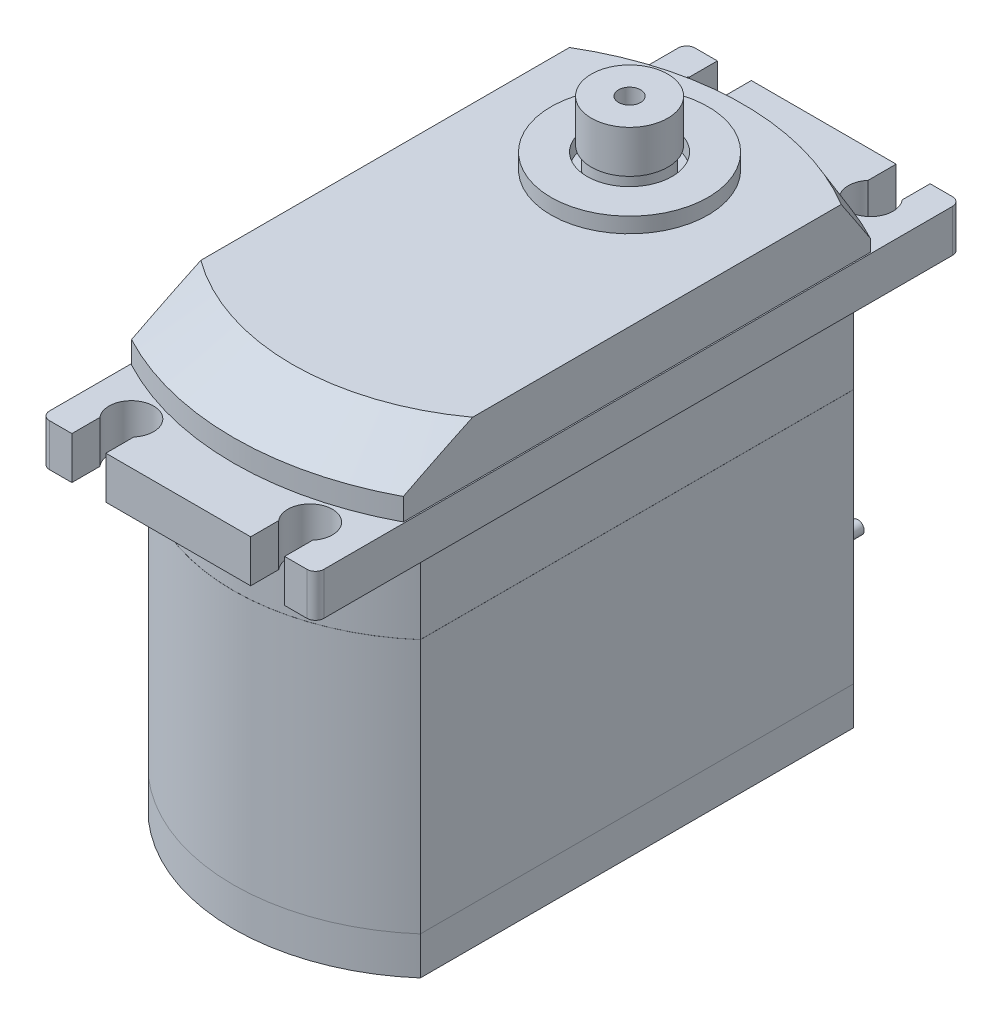
SolidWorks part; units mm, degrees
ref_plane "Front Plane" through (0, 0, 0) normal (0, 0, 1) x (1, 0, 0)
ref_plane "Top Plane" through (0, 0, 0) normal (0, 1, 0) x (1, 0, 0)
ref_plane "Right Plane" through (0, 0, 0) normal (1, 0, 0) x (0, 0, -1)
sketch "Sketch1" plane through (0, 0, 0) normal (0, 1, 0) x (1, 0, 0)
  line L1 (-16, 31.5) -> (16, 31.5)
  line L2 (-16, 31.5) -> (-16, -31.5)
  line L3 (-16, -31.5) -> (16, -31.5)
  line L4 (16, 31.5) -> (16, -31.5)
  line L5 (-16, 31.5) -> (16, -31.5) construction
  line L6 (-16, -31.5) -> (16, 31.5) construction
  point P0 (0, 0)
  dimension "D1" = 63
  dimension "32" = 32
extrude "Boss-Extrude1" add sketch "Sketch1" along normal blind 35
sketch "Sketch2" plane through (0, 35, 0) normal (0, 1, 0) x (1, 0, 0)
  line L1 (-16.5, 31.5) -> (16.5, 31.5)
  line L2 (-16.5, 31.5) -> (-16.5, -31.5)
  line L3 (-16.5, -31.5) -> (16.5, -31.5)
  line L4 (16.5, 31.5) -> (16.5, -31.5)
  line L5 (-16.5, 31.5) -> (16.5, -31.5) construction
  line L6 (-16.5, -31.5) -> (16.5, 31.5) construction
  point P0 (0, 0)
  dimension "D1" = 63
  dimension "sfds" = 33
extrude "Boss-Extrude2" add sketch "Sketch2" along normal blind 7.5
sketch "Sketch4" plane through (0, 42.5, 0) normal (0, 1, 0) x (1, 0, 0)
  line L0 (10.525, -33) -> (16.15, -33)
  line L1 (-16.15, -38) -> (16.15, -38)
  line L2 (-16.15, -38) -> (-16.15, 38)
  line L3 (-16.15, 38) -> (16.15, 38)
  line L4 (16.15, -38) -> (16.15, 38)
  line L5 (-16.15, -38) -> (16.15, 38) construction
  line L6 (-16.15, 38) -> (16.15, -38) construction
  line L7 (-10.525, -33) -> (-16.15, -33)
  line L8 (-10.525, 33) -> (-16.15, 33)
  line L9 (10.525, 33) -> (16.15, 33)
  line L10 (-10.525, -33) -> (-10.525, -38)
  line L11 (10.525, -33) -> (10.525, -38)
  line L12 (-10.525, 33) -> (-10.525, 38)
  line L13 (10.525, 33) -> (10.525, 38)
  line L14 (-12.525, -33) -> (-8.525, -33)
  line L15 (-8.525, -33) -> (-8.525, -38)
  line L16 (-12.525, -33) -> (-12.525, -38)
  line L17 (8.525, -33) -> (12.525, -33)
  line L18 (8.525, -33) -> (8.525, -38)
  line L19 (12.525, -33) -> (12.525, -38)
  line L20 (8.525, 33) -> (12.525, 33)
  line L21 (8.525, 33) -> (8.525, 38)
  line L22 (12.525, 33) -> (12.525, 38)
  line L23 (-12.525, 33) -> (-8.525, 33)
  line L24 (-8.525, 33) -> (-8.525, 38)
  line L25 (-12.525, 33) -> (-12.525, 38)
  circle A0 centre (-10.525, -33) radius 2.625
  circle A1 centre (10.525, -33) radius 2.625
  circle A2 centre (-10.525, 33) radius 2.625
  circle A3 centre (10.525, 33) radius 2.625
  point P0 (0, 0)
  point P26 (-10.525, -33)
  point P31 (10.525, -33)
  point P36 (10.525, 33)
  point P41 (-10.525, 33)
  line M18 (16.5, 31.5) -> (-16.5, 31.5)
  line M20 (-16.5, -31.5) -> (16.5, -31.5)
  dimension "D3" = 5.25
  dimension "D1" = 32.3
  dimension "D2" = 76
  dimension "D4" = 5.625
  dimension "D5" = 5
  dimension "D6" = 4
extrude "Boss-Extrude3" add sketch "Sketch4" along normal blind 5 contours A3 A2 L2 A0 A1 L4 M18 M20 | A1 A0 L15 L1 L18 M20 | A1 L0 L4 M20 | A1 L19 L1 L4 L0 | A0 L7 L2 L1 L16 | A0 L2 L7 M20 | A3 L9 L4 L3 L22 | A3 L4 L9 M18 | A3 L21 L3 L24 A2 M18 | A2 L8 L2 M18 | A2 L25 L3 L2 L8
sketch "Sketch5" plane through (0, 0, 0) normal (0, -1, 0) x (1, 0, 0)
  line L0 (-16, 31.5) -> (-16, 25.5) construction
  line L1 (-16, -31.5) -> (-16, 31.5) construction
  line L2 (-16, 25.5) -> (16, 25.5) construction
  line L3 (16, 31.5) -> (16, -31.5) construction
  line L4 (-16, 25.5) -> (16, 25.5)
  line L5 (0, 0) -> (26.1887, 0) construction
  line L6 (-16, -25.5) -> (16, -25.5)
  arc A0 (-16, 25.5) -> (16, 25.5) centre (0, 7.1667) cw
  arc A1 (-16, -25.5) -> (16, -25.5) centre (0, -7.1667) ccw
  line M3 (16, -31.5) -> (16, 31.5)
  line M4 (16, 31.5) -> (-16, 31.5)
  line M5 (-16, 31.5) -> (-16, -31.5)
  line M6 (-16, -31.5) -> (16, -31.5)
  dimension "D1" = 6
extrude "Cut-Extrude2" cut sketch "Sketch5" against normal up to surface (42.5 mm away) contours A0 M4 M3 | A0 M5 M4 | A1 M5 M6 | A1 M6 M3 up to face at (14.1148, 42.5, -34.7453)
sketch "Sketch6" plane through (-16.5, 0, 0) normal (-1, 0, 0) x (0, 0, 1)
  line L1 (-31.5, 42.5) -> (31.5, 42.5)
  line L2 (-31.5, 42.5) -> (-31.5, 35)
  line L3 (-31.5, 35) -> (31.5, 35)
  line L4 (31.5, 42.5) -> (31.5, 35)
extrude "Cut-Extrude3" cut sketch "Sketch6" against normal blind 0.5
sketch "Sketch7" plane through (16.5, 0, 0) normal (1, 0, 0) x (0, 0, -1)
  line L1 (-31.5, 42.5) -> (31.5, 42.5)
  line L2 (-31.5, 42.5) -> (-31.5, 35)
  line L3 (-31.5, 35) -> (31.5, 35)
  line L4 (31.5, 42.5) -> (31.5, 35)
extrude "Cut-Extrude4" cut sketch "Sketch7" against normal blind 0.5
sketch "Sketch8" plane through (0, 47.5, 0) normal (0, 1, 0) x (1, 0, 0)
  line L0 (-16, -31.5) -> (-16, -27.5) construction
  line L1 (-16, -31.5) -> (16, -31.5)
  line L2 (-16, -31.5) -> (-16, 31.5)
  line L3 (-16, 31.5) -> (16, 31.5)
  line L4 (16, -31.5) -> (16, 31.5)
  line L5 (-16, -31.5) -> (16, 31.5) construction
  line L6 (-16, 31.5) -> (16, -31.5) construction
  line L7 (-16, -27.5) -> (16, -27.5) construction
  line L8 (0, 0) -> (-24.3268, 0) construction
  line L9 (-16, -27.5) -> (16, -27.5)
  line L10 (-16, 27.5) -> (16, 27.5)
  arc A0 (-16, -27.5) -> (16, -27.5) centre (0, 2.5) ccw
  arc A1 (-16, 27.5) -> (16, 27.5) centre (0, -2.5) cw
  point P0 (0, 0)
  dimension "D1" = 32
  dimension "D2" = 63
  dimension "4" = 4
extrude "Boss-Extrude4" add sketch "Sketch8" along normal blind 6.6 contours L10 L2 L9 L4 | A1 L10 | A0 L9
sketch "Sketch9" plane through (0, 54.1, 0) normal (0, 1, 0) x (1, 0, 0)
  circle A0 centre (0, 15.1385) radius 5
  circle A1 centre (0, 15.1385) radius 9.25
  dimension "D1" = 18.5
  dimension "D2" = 10
extrude "Boss-Extrude5" add sketch "Sketch9" along normal blind 1.8
sketch "Sketch10" plane through (0, 54.1, 0) normal (0, 1, 0) x (1, 0, 0)
  circle A0 centre (0, 15.1385) radius 4
  dimension "D1" = 8
extrude "Boss-Extrude6" add sketch "Sketch10" along normal blind 2.5
sketch "Sketch11" plane through (0, 56.6, 0) normal (0, 1, 0) x (1, 0, 0)
  circle A0 centre (0, 15.1385) radius 4.5
  circle A1 centre (0, 15.1385) radius 1.3
  dimension "D1" = 9
  dimension "D2" = 2.6
extrude "Boss-Extrude7" add sketch "Sketch11" along normal blind 5
sketch "Sketch12" plane through (0, 0, 0) normal (0, 0, 1) x (1, 0, 0)
  line L0 (0, 0) -> (0, 19.2941) construction
  line L1 (3.75, 3.5) -> (-3.75, 3.5)
  line L2 (3.75, 3.5) -> (3.75, 8)
  line L3 (3.75, 8) -> (-3.75, 8)
  line L4 (-3.75, 3.5) -> (-3.75, 8)
  line L5 (3.75, 3.5) -> (-3.75, 8) construction
  line L6 (3.75, 8) -> (-3.75, 3.5) construction
  line L7 (-16, 0) -> (16, 0) construction
  point P0 (0, 5.75)
  dimension "D1" = 7.5
  dimension "4.5" = 4.5
  dimension "3.5" = 3.5
extrude "Boss-Extrude8" add sketch "Sketch12" along normal blind 7 from offset 30.5
sketch "Sketch13" plane through (0, 0, 37.5) normal (0, 0, 1) x (1, 0, 0)
  line L0 (0, 15.0026) -> (0, 0) construction
  line L1 (-2.25, 6.5) -> (2.25, 6.5)
  line L2 (-2.25, 6.5) -> (-2.25, 5)
  line L3 (-2.25, 5) -> (2.25, 5)
  line L4 (2.25, 6.5) -> (2.25, 5)
  line L5 (-2.25, 6.5) -> (2.25, 5) construction
  line L6 (-2.25, 5) -> (2.25, 6.5) construction
  line L7 (-3.75, 5.75) -> (10.206, 5.75) construction
  line L8 (-3.75, 8) -> (-3.75, 3.5) construction
  circle A0 centre (-1.51, 5.75) radius 0.75
  circle A1 centre (0, 5.75) radius 0.75
  circle A2 centre (1.51, 5.75) radius 0.75
  point P0 (0, 5.75)
  dimension "D1" = 4.5
  dimension "D2" = 1.5
  dimension "D3" = 1.51
  dimension "1.51" = 1.51
extrude "Boss-Extrude11" add sketch "Sketch13" along normal blind 3 contours A0 L2 | A1 | L4 A2 | L2 A0 | L4 A2
sketch "Sketch14" plane through (-16, 0, 0) normal (-1, 0, 0) x (0, 0, 1)
  line L0 (-25.5, 0) -> (-25.5, 4.5)
  line L1 (-25.5, 42.5) -> (-25.5, 0) construction
  line L2 (25.5, 42.5) -> (25.5, 0) construction
  line L3 (-25.5, 4.5) -> (25.5, 4.5)
  line L4 (-25.5, 4.5) -> (-25.5, 34.5)
  line L5 (-25.5, 34.5) -> (25.5, 34.5)
  line L6 (25.5, 4.5) -> (25.5, 34.5)
  line M7 (25.5, 0) -> (25.5, 42.5)
  line M9 (-25.5, 42.5) -> (-25.5, 0)
  dimension "D1" = 4.5
  dimension "30" = 30
extrude "Boss-Extrude12" add sketch "Sketch14" along normal blind 0.01 contours L5 L3 M9 M7
sketch "Sketch15" plane through (16, 0, 0) normal (1, 0, 0) x (0, 0, -1)
  line L0 (-25.5, 0) -> (-25.5, 4.5)
  line L1 (-25.5, 42.5) -> (-25.5, 0) construction
  line L2 (25.5, 42.5) -> (25.5, 0) construction
  line L3 (-25.5, 4.5) -> (25.5, 4.5)
  line L4 (-25.5, 4.5) -> (-25.5, 34.5)
  line L5 (-25.5, 34.5) -> (25.5, 34.5)
  line L6 (25.5, 4.5) -> (25.5, 34.5)
  line M2 (25.5, 0) -> (25.5, 42.5)
  line M4 (-25.5, 42.5) -> (-25.5, 0)
  dimension "D1" = 4.5
  dimension "D2" = 30
extrude "Boss-Extrude13" add sketch "Sketch15" along normal blind 0.01 contours L5 L3 M4 M2
chamfer "Chamfer1" distance 4 angle 60 1 edges at (0, 54.1, 31.5)
chamfer "Chamfer2" distance 3 angle 60 1 edges at (0, 54.1, -31.5)
sketch "Sketch19" plane through (0, 3.5, 0) normal (0, -1, 0) x (1, 0, 0)
  line L0 (-3.75, 37.5) -> (-3.75, 43.9945)
  line L1 (-3.75, 43.9945) -> (6.5687, 45.4193)
  line L2 (6.5687, 45.4193) -> (3.75, 37.5)
  line L3 (3.75, 37.5) -> (3.75, 31.2093)
  line L4 (-3.75, 37.5) -> (-3.75, 31.2093)
  line L5 (-3.75, 37.5) -> (-3.75, 31.2093) construction
  arc A0 (3.75, 31.2093) -> (-3.75, 31.2093) centre (0, 7.1667) ccw construction
  arc A1 (-3.75, 31.2093) -> (3.75, 31.2093) centre (0, 7.1667) cw
extrude "Cut-Extrude7" cut sketch "Sketch19" against normal up to surface (4.5 mm away) up to face at (0, 8, 34.4273)
sketch "Sketch17" plane through (0, 0, 0) normal (0, -1, 0) x (1, 0, 0)
  line L0 (-16, 25.5) -> (16, 25.5)
  line L1 (-16.0266, 25.49) -> (16.0266, 25.49)
  arc A0 (-16, 25.5) -> (16, 25.5) centre (0, 7.1667) cw
  arc A1 (-16.0266, 25.49) -> (16.0266, 25.49) centre (0, 7.1667) cw
  dimension "D1" = 0.01
extrude "Boss-Extrude15" add sketch "Sketch17" against normal blind 30 from offset 4.5 offset against normal yes
mirror "Mirror1" about plane through (0, 0, 0) normal (0, 0, 1) of "Boss-Extrude15"
fillet "Fillet3" radius 1 4 edges at (-16.15, 45, -38) (16.15, 45, -38) (-16.15, 45, 38) (16.15, 45, 38)
mirror "Mirror2" about plane through (0, 0, 0) normal (0, 0, 1) of "Boss-Extrude11", "Boss-Extrude8"
